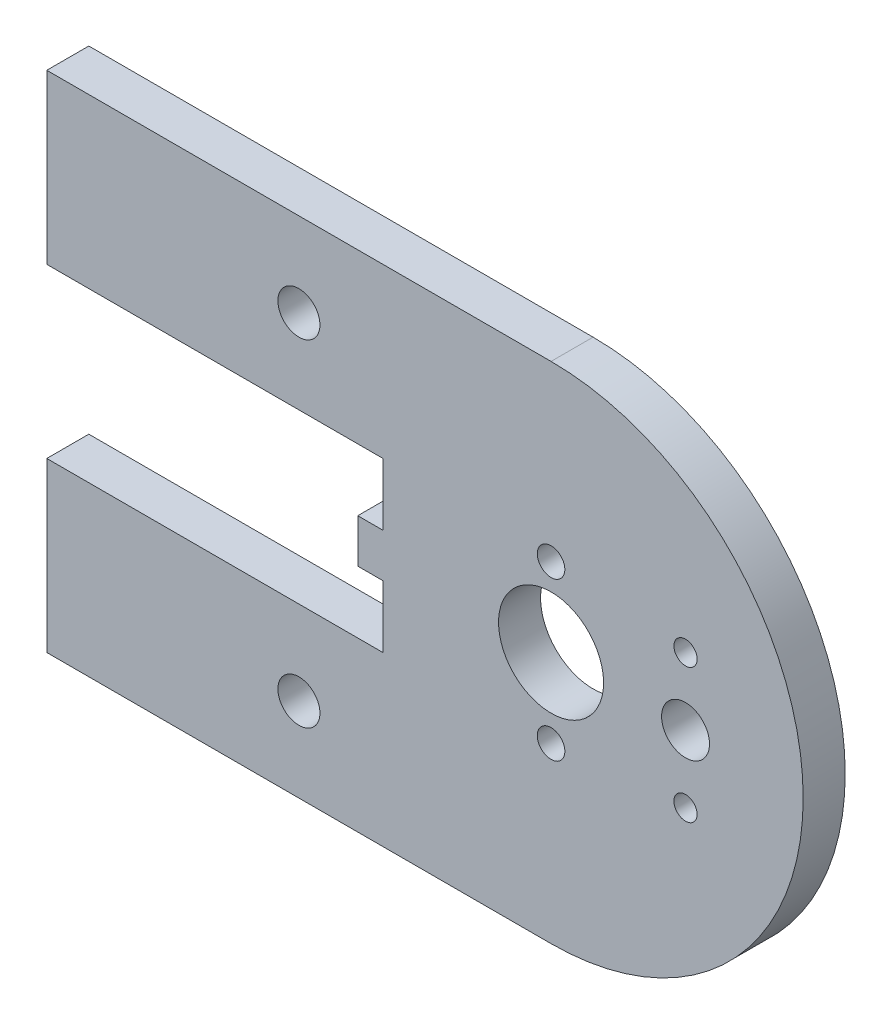
SolidWorks part; units mm, degrees
material "Beech"
ref_plane "Front Plane" through (0, 0, 0) normal (0, 0, 1) x (1, 0, 0)
ref_plane "Top Plane" through (0, 0, 0) normal (0, 1, 0) x (1, 0, 0)
ref_plane "Right Plane" through (0, 0, 0) normal (1, 0, 0) x (0, 0, -1)
sketch "Sketch1" plane through (0, 0, 0) normal (0, 0, 1) x (1, 0, 0)
  line L1 (-38.1, -38.1) -> (38.1, -38.1)
  line L2 (-38.1, -38.1) -> (-38.1, 38.1)
  line L3 (-38.1, 38.1) -> (38.1, 38.1)
  line L5 (-38.1, -38.1) -> (38.1, 38.1) construction
  line L6 (-38.1, 38.1) -> (38.1, -38.1) construction
  arc A0 (38.1, 38.1) -> (38.1, -38.1) centre (38.1, 0) cw
  point P0 (0, 0)
  dimension "D1" = 76.2
  dimension "D2" = 76.2
extrude "Boss-Extrude1" add sketch "Sketch1" along normal blind 6.35 contours L3 A0 L1 L2
sketch "Sketch2" plane through (0, 0, 6.35) normal (0, 0, 1) x (1, 0, 0)
  line L0 (-38.1, 0) -> (12.7, 0) construction
  line L1 (-38.1, 12.7) -> (12.7, 12.7)
  line L2 (-38.1, 12.7) -> (-38.1, -12.7)
  line L3 (-38.1, -12.7) -> (12.7, -12.7)
  line L4 (12.7, 12.7) -> (12.7, -12.7)
  line L5 (-38.1, -38.1) -> (-38.1, 38.1) construction
  point P0 (0, 0)
  dimension "D1" = 25.4
  dimension "D2" = 12.7
extrude "Cut-Extrude1" cut sketch "Sketch2" against normal through all
sketch "Sketch3" plane through (0, 0, 6.35) normal (0, 0, 1) x (1, 0, 0)
  line L0 (-38.1, -38.1) -> (38.1, -38.1) construction
  line L1 (-25.4, -38.1) -> (-12.7, -38.1)
  line L2 (-25.4, -38.1) -> (-25.4, -33.3375)
  line L3 (-25.4, -33.3375) -> (-20.574, -33.3375)
  line L4 (-12.7, -38.1) -> (-12.7, -33.3375)
  line L5 (-3.81, 38.1) -> (-3.81, -38.1) construction
  line L6 (19.05, -38.1) -> (19.05, 38.1) construction
  line L7 (-19.05, -38.1) -> (-19.05, 38.1) construction
  line L8 (-38.1, 38.1) -> (38.1, 38.1) construction
  line L9 (-19.05, 38.1) -> (11.43, 38.1) construction
  line L10 (0, 0) -> (42.8175, 0) construction
  line L11 (0, -38.1) -> (0, 38.1) construction
  line L12 (12.7, -38.1) -> (25.4, -38.1)
  line L13 (12.7, -38.1) -> (12.7, -33.3375)
  line L14 (12.7, -33.3375) -> (17.526, -33.3375)
  line L15 (25.4, -38.1) -> (25.4, -33.3375)
  line L16 (20.574, -33.3375) -> (25.4, -33.3375)
  line L17 (20.574, -33.3375) -> (20.574, -28.2575)
  line L18 (20.574, -21.9075) -> (17.526, -21.9075)
  line L19 (-17.526, -33.3375) -> (-12.7, -33.3375)
  line L20 (-17.526, -33.3375) -> (-17.526, -28.2575)
  line L21 (-17.526, -21.9075) -> (-20.574, -21.9075)
  line L22 (-20.574, -33.3375) -> (-20.574, -28.2575)
  line L23 (-20.574, -28.2575) -> (-22.86, -28.2575)
  line L24 (-22.86, -28.2575) -> (-22.86, -25.7175)
  line L25 (-22.86, -25.7175) -> (-20.574, -25.7175)
  line L26 (-20.574, -25.7175) -> (-20.574, -21.9075)
  line L27 (-17.526, -28.2575) -> (-15.24, -28.2575)
  line L28 (-15.24, -28.2575) -> (-15.24, -25.7175)
  line L29 (-15.24, -25.7175) -> (-17.526, -25.7175)
  line L30 (-17.526, -25.7175) -> (-17.526, -21.9075)
  line L31 (17.526, -33.3375) -> (17.526, -28.2575)
  line L32 (17.526, -28.2575) -> (15.24, -28.2575)
  line L33 (15.24, -25.7175) -> (17.526, -25.7175)
  line L34 (17.526, -25.7175) -> (17.526, -21.9075)
  line L35 (20.574, -28.2575) -> (22.86, -28.2575)
  line L36 (22.86, -28.2575) -> (22.86, -25.7175)
  line L37 (22.86, -25.7175) -> (20.574, -25.7175)
  line L38 (20.574, -25.7175) -> (20.574, -21.9075)
  line L39 (15.24, -25.7175) -> (15.24, -28.2575)
  dimension "D1" = 4.7625
  dimension "D2" = 3.81
  dimension "D3" = 4.826
  dimension "D4" = 19.05
  dimension "D5" = 19.05
  dimension "D7" = 4.826
  dimension "D8" = 11.43
  dimension "D10" = 3.048
  dimension "D11" = 5.08
  dimension "D12" = 2.54
  dimension "D13" = 2.286
  dimension "D14" = 5.08
  dimension "D15" = 2.54
  dimension "D16" = 2.286
  dimension "D17" = 12.7
sketch "Sketch4" plane through (0, 0, 6.35) normal (0, 0, 1) x (1, 0, 0)
  line L2 (0, 0) -> (0, -25.4) construction
  circle A3 centre (0, -25.4) radius 3.175
  point P16 (0, 0)
  dimension "D1" = 25.4
  dimension "D2" = 6.35
sketch "Sketch5" plane through (0, 0, 6.35) normal (0, 0, 1) x (1, 0, 0)
  line L0 (38.1, -11.8999) -> (38.1, 11.8999) construction
  line L1 (0, 0) -> (38.1, 0) construction
  circle A0 centre (38.1, 0) radius 7.9375
  circle A1 centre (38.1, 11.8999) radius 2.0828
  circle A2 centre (38.1, -11.8999) radius 2.0828
  point P9 (38.1, 0)
  dimension "D1" = 15.875
  dimension "D3" = 4.1656
  dimension "D2" = 23.7998
extrude "Cut-Extrude4" cut sketch "Sketch5" against normal through all
extrude "Cut-Extrude5" cut sketch "Sketch4" against normal through all
ref_plane "Plane1" through (0, 0, 0) normal (1, 0, 0) x (0, 0, -1)
mirror "Mirror3" about plane through (0, 0, 0) normal (0, 1, 0) of "Cut-Extrude5"
sketch "Sketch6" plane through (12.7, 0, 0) normal (-1, 0, 0) x (0, 0, 1)
  line L0 (0, 0) -> (6.35, 0) construction
  line L1 (0, -12.7) -> (0, 12.7) construction
  line L2 (6.35, -12.7) -> (6.35, 12.7) construction
  line L4 (0, 3.302) -> (6.35, 3.302)
  line L5 (0, 3.302) -> (0, -3.302)
  line L6 (0, -3.302) -> (6.35, -3.302)
  line L7 (6.35, 3.302) -> (6.35, -3.302)
  line L8 (0, 3.302) -> (6.35, -3.302) construction
  line L9 (0, -3.302) -> (6.35, 3.302) construction
  point P6 (3.175, 0)
  dimension "D1" = 6.604
extrude "Boss-Extrude2" add sketch "Sketch6" along normal blind 3.81
sketch "Sketch7" plane through (0, 0, 6.35) normal (0, 0, 1) x (1, 0, 0)
  line L0 (0, 0) -> (38.1, 0) construction
  line L1 (38.1, 11.8999) -> (38.1, -11.8999) construction
  line L2 (26.67, 3.6195) -> (31.0358, 3.6195)
  line L3 (26.67, -3.6195) -> (31.0358, -3.6195)
  arc A0 (26.67, 3.6195) -> (26.67, -3.6195) centre (26.67, 0) ccw
  circle A1 centre (38.1, 0) radius 7.9375 construction
  arc A2 (31.0358, 3.6195) -> (31.0358, -3.6195) centre (38.1, 0) ccw
  dimension "D1" = 7.239
  dimension "D2" = 11.43
extrude "Cut-Extrude6" [suppressed] cut sketch "Sketch7" against normal up to next
sketch "Sketch11" [suppressed] plane through (0, 0, 6.35) normal (0, 0, 1) x (1, 0, 0)
  line L0 (-38.1, -38.1) -> (38.1, -38.1) construction
  line L1 (-25.4, -38.1) -> (-12.7, -38.1)
  line L2 (-25.4, -38.1) -> (-25.4, -31.75)
  line L3 (-25.4, -31.75) -> (-20.9486, -31.75)
  line L4 (-12.7, -38.1) -> (-12.7, -31.75)
  line L5 (-25.4, -38.1) -> (-12.7, -31.75) construction
  line L6 (-25.4, -31.75) -> (-12.7, -38.1) construction
  line L7 (-38.1, -38.1) -> (-38.1, -12.7) construction
  line L8 (-20.9486, -31.75) -> (-20.9486, -28.2496)
  line L9 (-20.9486, -28.2496) -> (-23.0187, -28.2496)
  line L10 (-23.0187, -28.2496) -> (-23.0187, -25.4714)
  line L11 (-23.0187, -25.4714) -> (-20.9486, -25.4714)
  line L12 (-20.9486, -25.4714) -> (-20.9486, -21.971)
  line L13 (-20.9486, -21.971) -> (-17.1513, -21.971)
  line L14 (-19.05, -38.1) -> (-19.05, -21.971) construction
  line L15 (-17.1513, -25.4714) -> (-17.1513, -21.971)
  line L16 (-15.0812, -25.4714) -> (-17.1513, -25.4714)
  line L17 (-15.0812, -28.2496) -> (-15.0812, -25.4714)
  line L18 (-17.1513, -28.2496) -> (-15.0812, -28.2496)
  line L19 (-17.1513, -31.75) -> (-17.1513, -28.2496)
  line L20 (-17.1513, -31.75) -> (-12.7, -31.75)
  point P0 (-19.05, -34.925)
  dimension "D1" = 12.7
  dimension "D2" = 6.35
  dimension "D3" = 19.05
  dimension "D4" = 9.779
  dimension "D5" = 2.7781
  dimension "D6" = 3.9688
  dimension "D7" = 3.7973
extrude "Cut-Extrude8" [suppressed] cut sketch "Sketch11" against normal through all
pattern_linear "LPattern1" [suppressed] count 2 spacing 38.1
mirror "Mirror4" [suppressed] about plane through (0, 0, 0) normal (0, 1, 0)
sketch "Sketch8" plane through (0, 0, 6.35) normal (0, 0, 1) x (1, 0, 0)
  line L0 (0, 0) -> (76.2, 0) construction
  line L1 (38.1, 11.8999) -> (38.1, -11.8999) construction
  arc A0 (38.1, -38.1) -> (38.1, 38.1) centre (38.1, 0) ccw construction
  circle A1 centre (58.42, 0) radius 3.6195
  dimension "D1" = 7.239
  dimension "D2" = 20.32
extrude "Cut-Extrude7" cut sketch "Sketch8" against normal up to next
hole_wizard "#6 Clearance Hole1" positions "Sketch10" profile "Sketch9" hole size "#6" standard "ANSI Inch" end condition up to next
sketch "Sketch10" plane through (0, 0, 0) normal (0, 0, -1) x (-1, 0, 0)
  line L0 (-58.42, 0) -> (-58.42, 3.6195) construction
  line L1 (-58.42, 0) -> (-54.8005, 0) construction
  circle A0 centre (-58.42, 0) radius 3.6195 construction
  point P0 (-58.42, 10.16)
  point P3 (-58.42, -10.16)
  dimension "D1" = 20.32
sketch "Sketch9" plane through (58.42, 10.16, 0) normal (1, 0, 0) x (0, 1, 0)
  line L0 (0, 0) -> (0, 6.35)
  line L1 (0, 6.35) -> (1.7526, 6.35)
  line L2 (1.7526, 6.35) -> (1.7526, 0)
  line L5 (1.7526, 0) -> (0, 0)
  line L11 (0, -6.35) -> (0, 107.95) construction
  dimension "Thru Hole Dia." = 3.5052
  dimension "Thru Hole Depth" = 6.35
